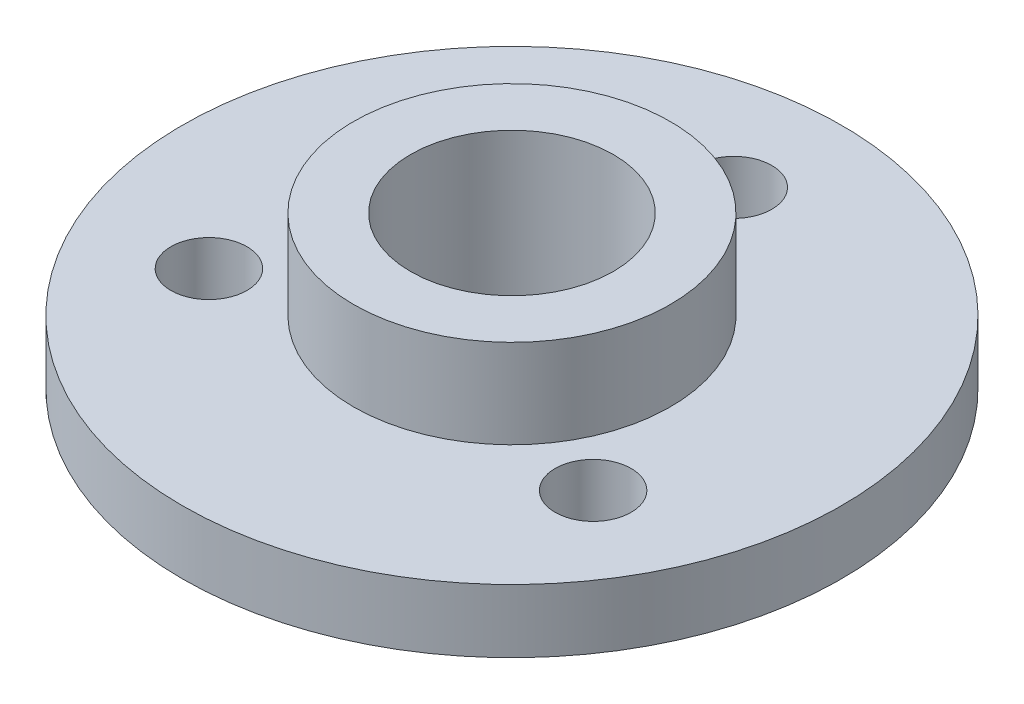
SolidWorks part; units mm, degrees
ref_plane "Front Plane" through (0, 0, 0) normal (0, 0, 1) x (1, 0, 0)
ref_plane "Top Plane" through (0, 0, 0) normal (0, 1, 0) x (1, 0, 0)
ref_plane "Right Plane" through (0, 0, 0) normal (1, 0, 0) x (0, 0, -1)
sketch "Sketch2" plane through (0, 0, 0) normal (0, 1, 0) x (1, 0, 0)
  circle A0 centre (0, 0) radius 26
  dimension "D1" = 52
extrude "Boss-Extrude1" add sketch "Sketch2" along normal blind 5
sketch "Sketch3" plane through (0, 5, 0) normal (0, 1, 0) x (1, 0, 0)
  circle A0 centre (0, 0) radius 12.5
  circle A1 centre (0, 0) radius 8
  dimension "D1" = 25
  dimension "D2" = 16
extrude "Boss-Extrude2" add sketch "Sketch3" along normal blind 7
sketch "Sketch4" plane through (0, 5, 0) normal (0, 1, 0) x (1, 0, 0)
  circle A0 centre (0, 0) radius 8 construction
  circle A1 centre (0, 0) radius 8
extrude "Cut-Extrude1" cut sketch "Sketch4" against normal through all
fillet "Fillet1" [suppressed] radius 2
sketch "Sketch6" plane through (0, 5, 0) normal (0, 1, 0) x (1, 0, 0)
  line L0 (0, 28.8288) -> (0, -28.3391) construction
  circle A0 centre (0, 0) radius 17.5 construction
  circle A1 centre (0, 17.5) radius 3
  circle A2 centre (15.1554, -8.75) radius 3
  circle A3 centre (-15.1554, -8.75) radius 3
  point P14 (0, 0)
  dimension "D1" = 35
  dimension "D2" = 6
  dimension "D3" = 3
extrude "Cut-Extrude2" cut sketch "Sketch6" against normal through all
